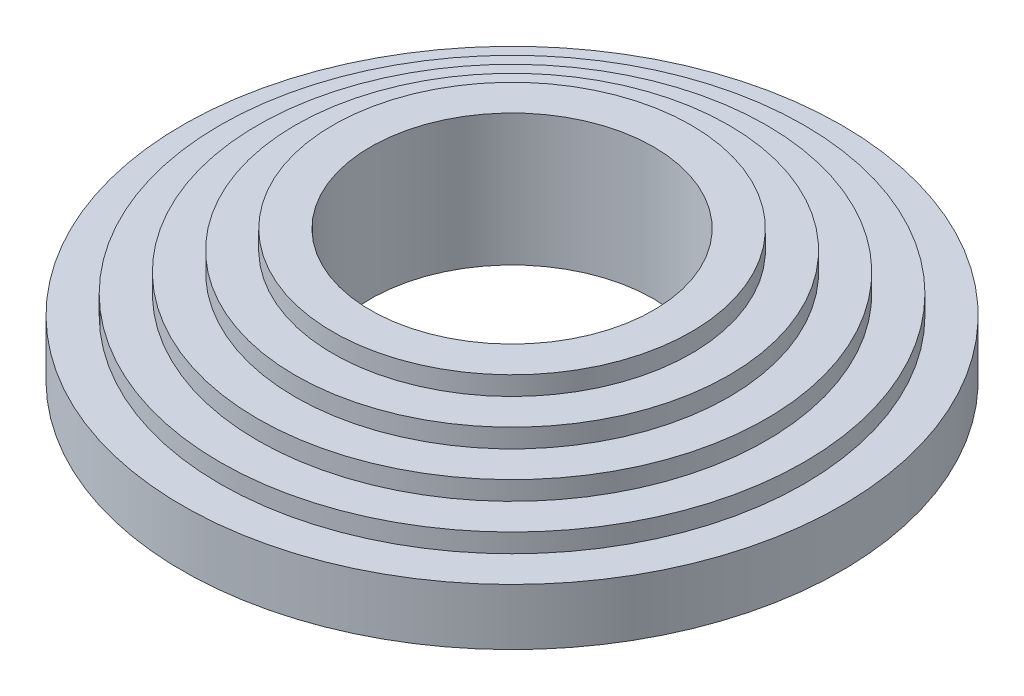
SolidWorks part; units mm, degrees
material "Copper"
ref_plane "Front Plane" through (0, 0, 0) normal (0, 0, 1) x (1, 0, 0)
ref_plane "Top Plane" through (0, 0, 0) normal (0, 1, 0) x (1, 0, 0)
ref_plane "Right Plane" through (0, 0, 0) normal (1, 0, 0) x (0, 0, -1)
sketch "Sketch1" plane through (0, 0, 0) normal (0, 0, 1) x (1, 0, 0)
  line L0 (0, 0) -> (0, 44.8786) construction
  line L1 (-44.734, 35.0971) -> (-36.972, 35.0971)
  line L2 (-44.734, 35.0971) -> (-44.734, 31.2161)
  line L3 (-44.734, 31.2161) -> (-52.496, 31.2161)
  line L4 (-52.496, 31.2161) -> (-52.496, 27.3351)
  line L5 (-52.496, 27.3351) -> (-60.258, 27.3351)
  line L6 (-60.258, 27.3351) -> (-60.258, 23.4541)
  line L7 (-60.258, 23.4541) -> (-68.02, 23.4541)
  line L8 (-68.02, 23.4541) -> (-68.02, 11.8111)
  line L9 (-68.02, 11.8111) -> (-29.21, 11.8111)
  line L10 (-29.21, 11.8111) -> (-29.21, 35.0971)
  line L11 (-36.972, 35.0971) -> (-36.972, 38.9781)
  line L12 (-36.972, 38.9781) -> (-29.21, 38.9781)
  line L13 (-29.21, 38.9781) -> (-29.21, 35.0971)
  dimension "D1" = 3.881
  dimension "D2" = 3.881
  dimension "D3" = 3.881
  dimension "D4" = 11.643
  dimension "D5" = 3.881
  dimension "D6" = 7.762
  dimension "D7" = 7.762
  dimension "D8" = 7.762
  dimension "D9" = 7.762
  dimension "D10" = 7.762
  dimension "D11" = 58.42
revolve "Revolve1" add sketch "Sketch1" angle 360 about L0
